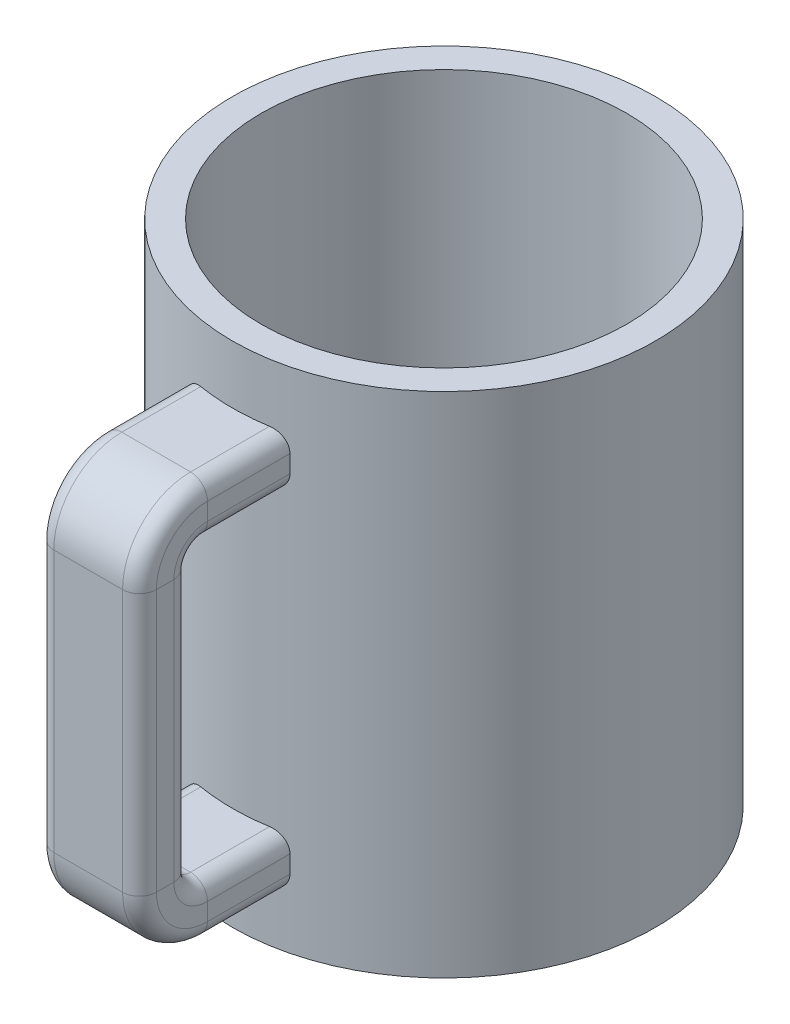
SolidWorks part; units mm, degrees
ref_plane "Plano frontal" through (0, 0, 0) normal (0, 0, 1) x (1, 0, 0)
ref_plane "Plano superior" through (0, 0, 0) normal (0, 1, 0) x (1, 0, 0)
ref_plane "Plano direito" through (0, 0, 0) normal (1, 0, 0) x (0, 0, -1)
sketch "Esboço2" plane through (0, 0, 0) normal (1, 0, 0) x (0, 0, -1)
  line L1 (0, 0) -> (-25, 0)
  line L2 (0, 0) -> (0, 60)
  line L3 (0, 60) -> (-25, 60)
  line L4 (-25, 0) -> (-25, 60)
  dimension "D1" = 60
  dimension "D2" = 25
revolve "Revolução1" add sketch "Esboço2" angle 360 about L2
sketch "Esboço3" plane through (0, 60, 0) normal (0, 1, 0) x (1, 0, 0)
  circle A0 centre (0, 0) radius 21.591
extrude "Corte-extrusão1" cut sketch "Esboço3" against normal blind 57
ref_plane "Plano1" through (0, 0, 28) normal (0, 0, 1) x (1, 0, 0)
sketch "Esboço4" plane through (0, 0, 28) normal (0, 0, 1) x (1, 0, 0)
  line L1 (-4.0623, 53.135) -> (4.0623, 53.135)
  line L2 (-6.0623, 51.135) -> (-6.0623, 49.0726)
  line L3 (-4.0623, 47.0726) -> (4.0623, 47.0726)
  line L4 (6.0623, 51.135) -> (6.0623, 49.0726)
  line L5 (-6.0623, 53.135) -> (6.0623, 47.0726) construction
  line L6 (-6.0623, 47.0726) -> (6.0623, 53.135) construction
  arc A0 (-4.0623, 53.135) -> (-6.0623, 51.135) centre (-4.0623, 51.135) ccw
  arc A5 (-6.0623, 49.0726) -> (-4.0623, 47.0726) centre (-4.0623, 49.0726) ccw
  arc A6 (4.0623, 47.0726) -> (6.0623, 49.0726) centre (4.0623, 49.0726) ccw
  arc A7 (4.0623, 53.135) -> (6.0623, 51.135) centre (4.0623, 51.135) cw
  point P0 (0, 50.1038)
  point P7 (0, 47.0726)
  dimension "D1" = 2
sketch "Esboço5" plane through (0, 0, 0) normal (1, 0, 0) x (0, 0, -1)
  line L0 (-28, 50.1038) -> (-34, 50.1038)
  line L1 (-39, 45.1038) -> (-39, 14.1503)
  line L2 (-34, 9.1503) -> (-28, 9.1503)
  line L3 (-28, 27.5) -> (-28, -27.5) construction
  arc A0 (-39, 14.1503) -> (-34, 9.1503) centre (-34, 14.1503) ccw
  arc A1 (-34, 50.1038) -> (-39, 45.1038) centre (-34, 45.1038) ccw
  point P2 (-28.2456, 50.1771)
  point P5 (-28, 50.1038)
  point P11 (-28, 9.149)
  dimension "D1" = 5
  dimension "D2" = 6
sweep "Varredura1" add profiles "Esboço4" path "Esboço5"
sketch "Esboço6" plane through (0, 0, 28) normal (0, 0, -1) x (-1, 0, 0)
  line L4 (4.0623, 53.135) -> (-4.0623, 53.135)
  line L5 (-6.0623, 51.135) -> (-6.0623, 49.0726)
  line L6 (-4.0623, 47.0726) -> (4.0623, 47.0726)
  line L7 (6.0623, 49.0726) -> (6.0623, 51.135)
  line L8 (4.0623, 53.135) -> (-4.0623, 53.135)
  line L9 (-6.0623, 51.135) -> (-6.0623, 49.0726)
  line L10 (-4.0623, 47.0726) -> (4.0623, 47.0726)
  line L11 (6.0623, 49.0726) -> (6.0623, 51.135)
  line L12 (6.0623, 8.1191) -> (6.0623, 10.1814)
  line L13 (4.0623, 12.1814) -> (-4.0623, 12.1814)
  line L14 (-6.0623, 10.1814) -> (-6.0623, 8.1191)
  line L15 (-4.0623, 6.1191) -> (4.0623, 6.1191)
  line L16 (6.0623, 8.1191) -> (6.0623, 10.1814)
  line L17 (4.0623, 12.1814) -> (-4.0623, 12.1814)
  line L18 (-6.0623, 10.1814) -> (-6.0623, 8.1191)
  line L19 (-4.0623, 6.1191) -> (4.0623, 6.1191)
  arc A4 (6.0623, 51.135) -> (4.0623, 53.135) centre (4.0623, 51.135) ccw
  arc A5 (-4.0623, 53.135) -> (-6.0623, 51.135) centre (-4.0623, 51.135) ccw
  arc A6 (-6.0623, 49.0726) -> (-4.0623, 47.0726) centre (-4.0623, 49.0726) ccw
  arc A7 (4.0623, 47.0726) -> (6.0623, 49.0726) centre (4.0623, 49.0726) ccw
  arc A8 (6.0623, 51.135) -> (4.0623, 53.135) centre (4.0623, 51.135) ccw
  arc A9 (-4.0623, 53.135) -> (-6.0623, 51.135) centre (-4.0623, 51.135) ccw
  arc A10 (-6.0623, 49.0726) -> (-4.0623, 47.0726) centre (-4.0623, 49.0726) ccw
  arc A11 (4.0623, 47.0726) -> (6.0623, 49.0726) centre (4.0623, 49.0726) ccw
  arc A12 (4.0623, 6.1191) -> (6.0623, 8.1191) centre (4.0623, 8.1191) ccw
  arc A13 (6.0623, 10.1814) -> (4.0623, 12.1814) centre (4.0623, 10.1814) ccw
  arc A14 (-4.0623, 12.1814) -> (-6.0623, 10.1814) centre (-4.0623, 10.1814) ccw
  arc A15 (-6.0623, 8.1191) -> (-4.0623, 6.1191) centre (-4.0623, 8.1191) ccw
  arc A16 (4.0623, 6.1191) -> (6.0623, 8.1191) centre (4.0623, 8.1191) ccw
  arc A17 (6.0623, 10.1814) -> (4.0623, 12.1814) centre (4.0623, 10.1814) ccw
  arc A18 (-4.0623, 12.1814) -> (-6.0623, 10.1814) centre (-4.0623, 10.1814) ccw
  arc A19 (-6.0623, 8.1191) -> (-4.0623, 6.1191) centre (-4.0623, 8.1191) ccw
  dimension "D1" = 0
  dimension "D2" = 0
extrude "Ressalto-extrusão1" add sketch "Esboço6" along normal up to next
